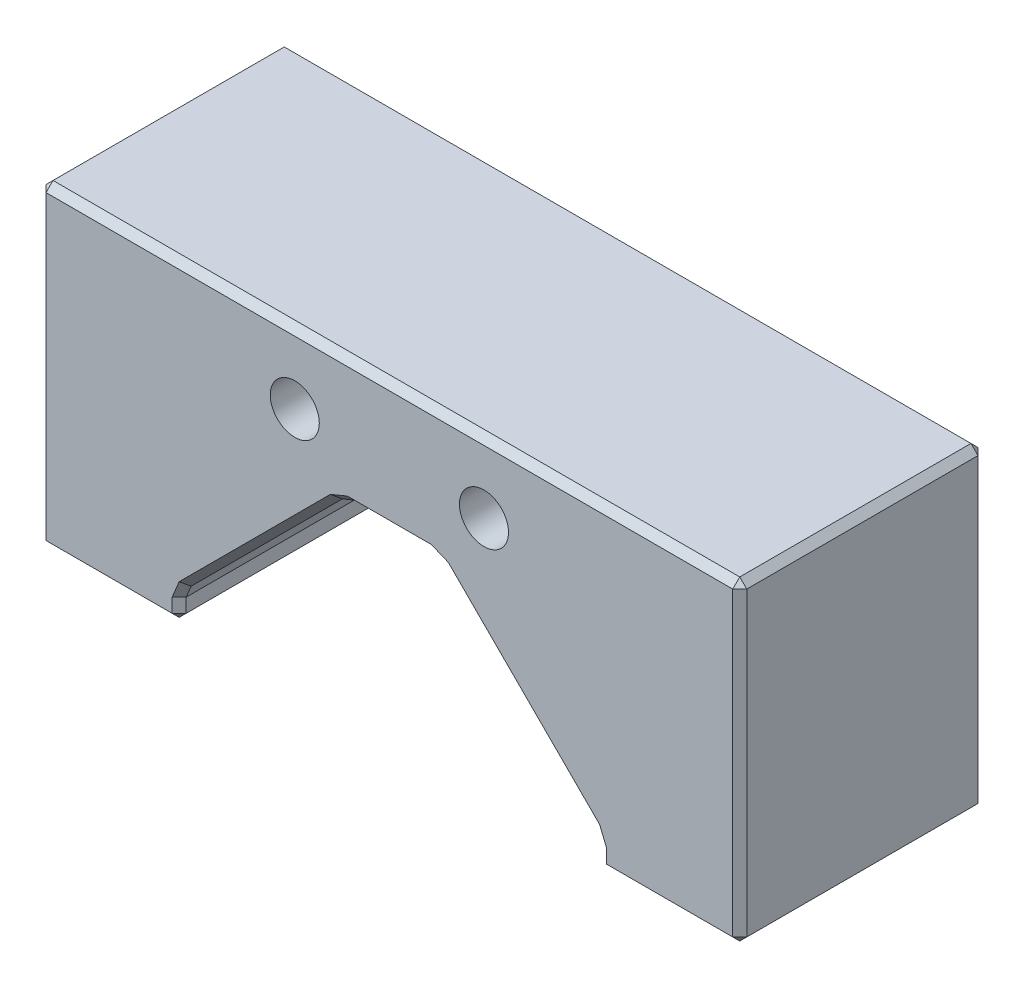
SolidWorks part; units mm, degrees
material "6061 Alloy"
ref_plane "Front Plane" through (0, 0, 0) normal (0, 0, 1) x (1, 0, 0)
ref_plane "Top Plane" through (0, 0, 0) normal (0, 1, 0) x (1, 0, 0)
ref_plane "Right Plane" through (0, 0, 0) normal (1, 0, 0) x (0, 0, -1)
sketch "Sketch1" plane through (0, 0, 0) normal (0, 0, 1) x (1, 0, 0)
  line L0 (0, 0) -> (0, -38.2305) construction
  line L1 (50, 0) -> (-50, 0)
  line L2 (-50, 0) -> (-50, -45)
  line L3 (-50, -45) -> (-30, -45)
  line L4 (-30, -45) -> (-30, -41)
  line L5 (-30, -41) -> (-7, -18)
  line L6 (-7, -18) -> (7, -18)
  line L7 (30, -41) -> (7, -18)
  line L8 (30, -45) -> (30, -41)
  line L9 (50, -45) -> (30, -45)
  line L10 (50, 0) -> (50, -45)
  point P10 (0, -18)
  dimension "D1" = 100
  dimension "D2" = 45
  dimension "D3" = 20
  dimension "D4" = 4
  dimension "D5" = 27
  dimension "D6" = 90
extrude "Boss-Extrude1" add sketch "Sketch1" along normal blind 35
chamfer "Chamfer1" distance 1 30 edges at (30, -41, 17.5) (-30, -41, 17.5) (-7, -18, 17.5) (7, -18, 17.5) (30, -45, 17.5) (50, -45, 17.5) (50, 0, 17.5) (-50, 0, 17.5) (-50, -45, 17.5) (0, -18, 35) (-18.5, -29.5, 35) (-30, -43, 35) (18.5, -29.5, 35) (30, -43, 35) (40, -45, 35) (50, -22.5, 35) (0, 0, 35) (-50, -22.5, 35) (-40, -45, 35) (-30, -45, 17.5) (0, -18, 0) (-18.5, -29.5, 0) (-30, -43, 0) (-40, -45, 0) (-50, -22.5, 0) (0, 0, 0) (50, -22.5, 0) (40, -45, 0) (30, -43, 0) (18.5, -29.5, 0)
hole_wizard "Ø7.0 (7) Diameter Hole1" positions "Sketch2" profile "Sketch3" hole size "Ø7.0" standard "ISO"
sketch "Sketch2" plane through (0, 0, 35) normal (0, 0, 1) x (1, 0, 0)
  line L0 (0, 0) -> (0, -26.8571) construction
  line L2 (6, -18) -> (-6, -18) construction
  point P0 (-13.5, -10)
  point P2 (13.5, -10)
  dimension "D1" = 27
  dimension "D2" = 8
sketch "Sketch3" plane through (-13.5, -10, 35) normal (1, 0, 0) x (0, -1, 0)
  line L0 (0, 0) -> (0, 14.103)
  line L1 (0, 14.103) -> (3.5, 12)
  line L2 (3.5, 12) -> (3.5, 0)
  line L5 (3.5, 0) -> (0, 0)
  line L10 (0, 14.103) -> (-3.5, 12) construction
  line L11 (0, -6.35) -> (0, 107.95) construction
  dimension "Hole Dia." = 7
  dimension "Hole Depth" = 12
  dimension "Drill Angle" = 118
